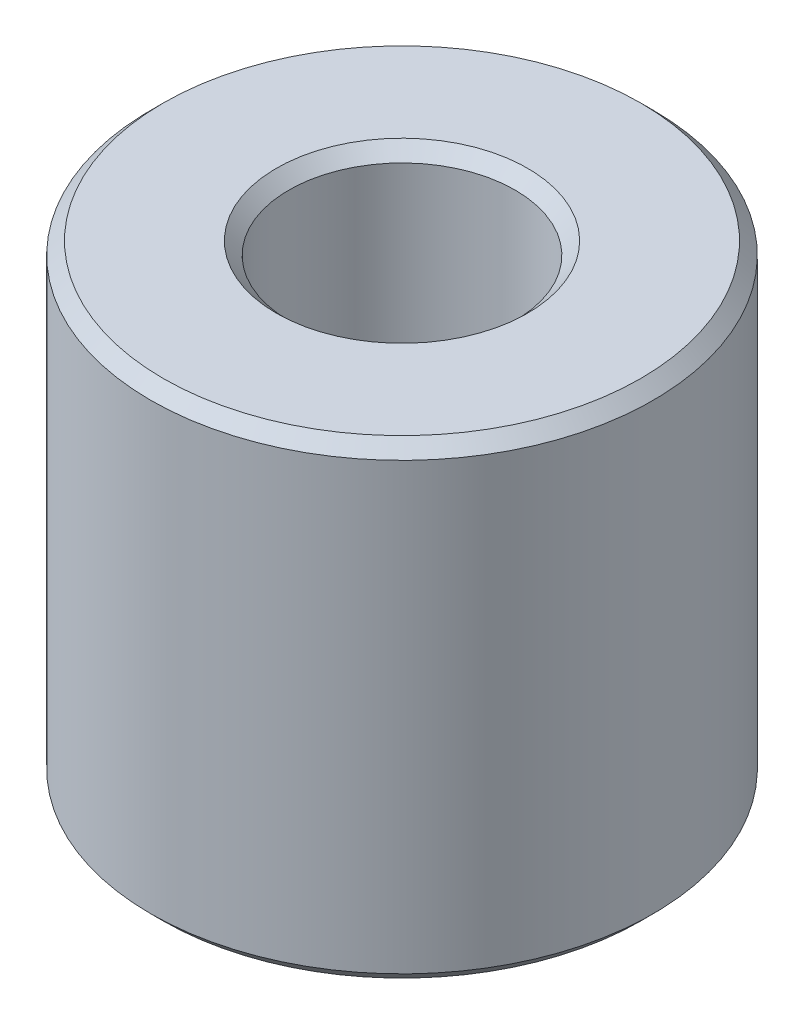
SolidWorks part; units mm, degrees
material "6061-T6 (SS)"
ref_plane "Front Plane" through (0, 0, 0) normal (0, 0, 1) x (1, 0, 0)
ref_plane "Top Plane" through (0, 0, 0) normal (0, 1, 0) x (1, 0, 0)
ref_plane "Right Plane" through (0, 0, 0) normal (1, 0, 0) x (0, 0, -1)
sketch "Sketch1" plane through (0, 0, 0) normal (0, 1, 0) x (1, 0, 0)
  circle A0 centre (0, 0) radius 4.5
  circle A1 centre (0, 0) radius 10
  dimension "D1" = 9
  dimension "D2" = 20
extrude "Body" add sketch "Sketch1" along normal blind 18.7
chamfer "Chamfer1" distance 0.5 angle 45 4 edges at (0, 0, 4.5) (0, 0, 10) (0, 18.7, 10) (0, 18.7, 4.5)
